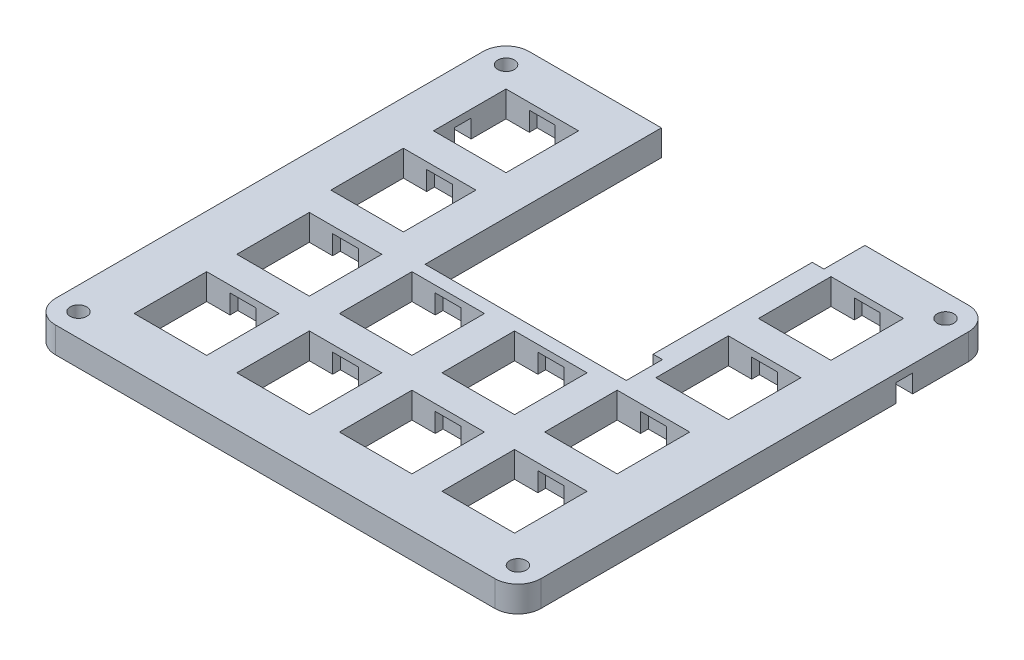
SolidWorks part; units mm, degrees
ref_plane "Front Plane" through (0, 0, 0) normal (0, 0, 1) x (1, 0, 0)
ref_plane "Top Plane" through (0, 0, 0) normal (0, 1, 0) x (1, 0, 0)
ref_plane "Right Plane" through (0, 0, 0) normal (1, 0, 0) x (0, 0, -1)
sketch "Sketch2" plane through (0, 0, 0) normal (0, 1, 0) x (1, 0, 0)
  line L6 (-46.8585, -41.275) -> (-46.8585, 41.275)
  line L8 (46.8585, -41.275) -> (46.8585, 41.275)
  line L9 (42.418, -45.7155) -> (-42.418, -45.7155)
  line L10 (-42.418, 45.7155) -> (-16.8754, 45.7155)
  line L12 (22.418, 41.275) -> (22.418, 39.575)
  line L13 (22.418, 39.575) -> (22.418, 37.7973)
  line L16 (42.418, 27.292) -> (38.3626, 27.292)
  line L18 (42.418, 30.492) -> (38.3626, 30.492)
  line L19 (42.418, 30.492) -> (46.218, 30.492)
  line L20 (46.218, 30.492) -> (46.218, 27.292)
  line L21 (46.218, 27.292) -> (42.418, 27.292)
  line L24 (-46.218, 28.892) -> (-46.218, 30.492)
  line L25 (-46.218, 30.492) -> (-38.3754, 30.492)
  line L26 (-46.218, 28.892) -> (-46.218, 27.292)
  line L27 (-46.218, 27.292) -> (-38.3754, 27.292)
  line L29 (20.1687, 37.7973) -> (20.1687, 9.575)
  line L30 (22.418, 37.7973) -> (20.1687, 37.7973)
  line L31 (20.1687, 9.575) -> (20.1687, 7.075)
  line L32 (20.1687, 7.075) -> (21.9687, 7.075)
  line L33 (-9.9124, 0.0949) -> (21.9687, 0.0949)
  line L35 (21.9687, 7.075) -> (21.9687, 0.0949)
  line L36 (22.418, 41.275) -> (22.418, 45.7155)
  line L38 (-16.8754, 30.2189) -> (-16.8754, 0.0949)
  line L39 (-16.8754, 0.0949) -> (-9.9124, 0.0949)
  line L40 (-16.8754, 30.2189) -> (-16.8754, 45.7155)
  line L41 (-31.3754, 37.2189) -> (-38.3754, 37.2189)
  line L42 (-38.3754, 37.2189) -> (-38.3754, 23.2189)
  line L43 (-38.3754, 23.2189) -> (-24.3754, 23.2189)
  line L44 (-24.3754, 23.2189) -> (-24.3754, 37.2189)
  line L45 (-24.3754, 37.2189) -> (-31.3754, 37.2189)
  line L47 (-38.3754, 10.4069) -> (-38.3754, 17.4069)
  line L48 (-38.3754, 17.4069) -> (-24.3754, 17.4069)
  line L49 (-24.3754, 17.4069) -> (-24.3754, 3.4069)
  line L50 (-24.3754, 3.4069) -> (-38.3754, 3.4069)
  line L51 (-38.3754, 3.4069) -> (-38.3754, 10.4069)
  line L53 (-36.7244, -9.4051) -> (-36.7244, -2.4051)
  line L54 (-36.7244, -2.4051) -> (-22.7244, -2.4051)
  line L55 (-22.7244, -2.4051) -> (-22.7244, -16.4051)
  line L56 (-22.7244, -16.4051) -> (-36.7244, -16.4051)
  line L57 (-36.7244, -16.4051) -> (-36.7244, -9.4051)
  line L59 (-36.7244, -29.2171) -> (-36.7244, -22.2171)
  line L60 (-36.7244, -22.2171) -> (-22.7244, -22.2171)
  line L61 (-22.7244, -22.2171) -> (-22.7244, -36.2171)
  line L62 (-22.7244, -36.2171) -> (-36.7244, -36.2171)
  line L63 (-36.7244, -36.2171) -> (-36.7244, -29.2171)
  line L65 (-9.9124, -22.2171) -> (-2.9124, -22.2171)
  line L66 (-2.9124, -22.2171) -> (-2.9124, -36.2171)
  line L67 (-2.9124, -36.2171) -> (-16.9124, -36.2171)
  line L68 (-16.9124, -36.2171) -> (-16.9124, -22.2171)
  line L69 (-16.9124, -22.2171) -> (-9.9124, -22.2171)
  line L71 (-9.9124, -16.4051) -> (-2.9124, -16.4051)
  line L72 (-2.9124, -16.4051) -> (-2.9124, -2.4051)
  line L73 (-2.9124, -2.4051) -> (-16.9124, -2.4051)
  line L74 (-16.9124, -2.4051) -> (-16.9124, -16.4051)
  line L75 (-16.9124, -16.4051) -> (-9.9124, -16.4051)
  line L77 (9.8996, -2.4051) -> (2.8996, -2.4051)
  line L78 (2.8996, -2.4051) -> (2.8996, -16.4051)
  line L79 (2.8996, -16.4051) -> (16.8996, -16.4051)
  line L80 (16.8996, -16.4051) -> (16.8996, -2.4051)
  line L81 (16.8996, -2.4051) -> (9.8996, -2.4051)
  line L83 (9.8996, -22.2171) -> (2.8996, -22.2171)
  line L84 (2.8996, -22.2171) -> (2.8996, -36.2171)
  line L85 (2.8996, -36.2171) -> (16.8996, -36.2171)
  line L86 (16.8996, -36.2171) -> (16.8996, -22.2171)
  line L87 (16.8996, -22.2171) -> (9.8996, -22.2171)
  line L89 (36.7116, -29.2171) -> (36.7116, -22.2171)
  line L90 (36.7116, -22.2171) -> (22.7116, -22.2171)
  line L91 (22.7116, -22.2171) -> (22.7116, -36.2171)
  line L92 (22.7116, -36.2171) -> (36.7116, -36.2171)
  line L93 (36.7116, -36.2171) -> (36.7116, -29.2171)
  line L95 (29.7116, -2.4051) -> (22.7116, -2.4051)
  line L96 (22.7116, -2.4051) -> (22.7116, -16.4051)
  line L97 (22.7116, -16.4051) -> (36.7116, -16.4051)
  line L98 (36.7116, -16.4051) -> (36.7116, -2.4051)
  line L99 (36.7116, -2.4051) -> (29.7116, -2.4051)
  line L101 (38.3626, 10.4069) -> (38.3626, 17.4069)
  line L102 (38.3626, 17.4069) -> (24.3626, 17.4069)
  line L103 (24.3626, 17.4069) -> (24.3626, 3.4069)
  line L104 (24.3626, 3.4069) -> (38.3626, 3.4069)
  line L105 (38.3626, 3.4069) -> (38.3626, 10.4069)
  line L106 (38.3626, 30.2189) -> (38.3626, 23.2189)
  line L107 (38.3626, 23.2189) -> (24.3626, 23.2189)
  line L108 (24.3626, 23.2189) -> (24.3626, 37.2189)
  line L109 (24.3626, 37.2189) -> (38.3626, 37.2189)
  line L110 (38.3626, 37.2189) -> (38.3626, 30.2189)
  line L111 (22.418, 45.7155) -> (42.418, 45.7155)
  arc A0 (-42.418, 45.7155) -> (-46.8585, 41.275) centre (-42.418, 41.275) ccw
  arc A1 (42.418, 45.7155) -> (46.8585, 41.275) centre (42.418, 41.275) cw
  arc A2 (-46.8585, -41.275) -> (-42.418, -45.7155) centre (-42.418, -41.275) ccw
  arc A3 (46.8585, -41.275) -> (42.418, -45.7155) centre (42.418, -41.275) cw
  circle A4 centre (42.418, 41.275) radius 1.6
  circle A5 centre (-42.418, 41.275) radius 1.6
  circle A6 centre (-42.418, -41.275) radius 1.6
  circle A7 centre (42.418, -41.275) radius 1.6
extrude "Boss-Extrude1" add sketch "Sketch2" along normal blind 5 contours A3 L8 A1 L111 L36 L12 L13 L30 L29 L31 L32 L35 L33 L39 L38 L40 L10 A0 L6 A2 L9 A7 A6 A5 A4 L105 L104 L103 L102 L101 L99 L98 L97 L96 L95 L93 L92 L91 L90 L89 L87 L86 L85 | L42 L25 L24 L26 L27 | L18 L110 L106 L16 L21 L20 L19
sketch "Sketch3" plane through (0, 0, 0) normal (0, -1, 0) x (1, 0, 0)
  line L0 (42.418, -41.275) -> (42.418, -28.892)
  line L1 (42.418, -28.892) -> (46.218, -28.892)
  line L3 (46.218, -27.292) -> (38.3626, -27.292)
  line L4 (38.3626, -37.2189) -> (38.3626, -23.2189) construction
  line L6 (46.218, -30.492) -> (38.3626, -30.492)
  line L7 (38.3626, -30.492) -> (38.3626, -27.292)
  line L8 (-42.418, -41.275) -> (-42.418, -28.892)
  line L9 (-42.418, -28.892) -> (-46.218, -28.892)
  line L12 (-46.218, -27.292) -> (-38.3754, -27.292)
  line L13 (-38.3754, -37.2189) -> (-38.3754, -23.2189) construction
  line L14 (-46.218, -30.492) -> (-38.3754, -30.492)
  line L15 (-38.3754, -30.492) -> (-38.3754, -27.292)
  line L16 (-46.218, -27.292) -> (-46.8585, -27.292)
  line L17 (-46.8585, 41.275) -> (-46.8585, -41.275) construction
  line L18 (-46.8585, -27.292) -> (-46.8585, -30.492)
  line L19 (-46.8585, -30.492) -> (-46.218, -30.492)
  line L20 (46.218, -27.292) -> (46.8585, -27.292)
  line L21 (46.8585, 41.275) -> (46.8585, -41.275) construction
  line L22 (46.8585, -27.292) -> (46.8585, -30.492)
  line L23 (46.8585, -30.492) -> (46.218, -30.492)
extrude "Cut-Extrude1" cut sketch "Sketch3" against normal blind 3.5
sketch "Sketch4" plane through (0, 0, 0) normal (0, -1, 0) x (1, 0, 0)
  line L0 (31.3626, -37.2189) -> (31.3626, -38.7189)
  line L1 (24.3626, -37.2189) -> (38.3626, -37.2189) construction
  line L2 (31.3626, -38.7189) -> (28.8626, -38.7189)
  line L3 (28.8626, -38.7189) -> (28.8626, -37.2189)
  line L4 (28.8626, -37.2189) -> (33.8626, -37.2189)
  line L5 (33.8626, -37.2189) -> (33.8626, -38.7189)
  line L6 (33.8626, -38.7189) -> (31.3626, -38.7189)
  line L7 (31.3626, -23.2189) -> (31.3626, -21.7189)
  line L8 (38.3626, -23.2189) -> (24.3626, -23.2189) construction
  line L9 (31.3626, -21.7189) -> (33.8626, -21.7189)
  line L10 (33.8626, -21.7189) -> (33.8626, -23.2189)
  line L11 (33.8626, -23.2189) -> (28.8626, -23.2189)
  line L12 (28.8626, -23.2189) -> (28.8626, -21.7189)
  line L13 (28.8626, -21.7189) -> (31.3626, -21.7189)
  line L14 (31.3626, -17.4069) -> (31.3626, -18.9069)
  line L15 (38.3626, -17.4069) -> (24.3626, -17.4069) construction
  line L16 (31.3626, -18.9069) -> (33.8626, -18.9069)
  line L17 (33.8626, -18.9069) -> (33.8626, -17.4069)
  line L18 (33.8626, -17.4069) -> (28.8626, -17.4069)
  line L19 (28.8626, -17.4069) -> (28.8626, -18.9069)
  line L20 (28.8626, -18.9069) -> (31.3626, -18.9069)
  line L21 (31.3626, -3.4069) -> (31.3626, -1.9069)
  line L22 (24.3626, -3.4069) -> (38.3626, -3.4069) construction
  line L23 (31.3626, -1.9069) -> (33.8626, -1.9069)
  line L24 (33.8626, -1.9069) -> (33.8626, -3.4069)
  line L25 (33.8626, -3.4069) -> (28.8626, -3.4069)
  line L26 (28.8626, -3.4069) -> (28.8626, -1.9069)
  line L27 (28.8626, -1.9069) -> (31.3626, -1.9069)
  line L28 (29.7116, 2.4051) -> (29.7116, 0.9051)
  line L29 (36.7116, 2.4051) -> (22.7116, 2.4051) construction
  line L30 (29.7116, 0.9051) -> (32.2116, 0.9051)
  line L31 (32.2116, 0.9051) -> (32.2116, 2.4051)
  line L32 (32.2116, 2.4051) -> (27.2116, 2.4051)
  line L33 (27.2116, 2.4051) -> (27.2116, 0.9051)
  line L34 (27.2116, 0.9051) -> (29.7116, 0.9051)
  line L35 (29.7116, 16.4051) -> (29.7116, 17.9051)
  line L36 (22.7116, 16.4051) -> (36.7116, 16.4051) construction
  line L37 (29.7116, 17.9051) -> (32.2116, 17.9051)
  line L38 (32.2116, 17.9051) -> (32.2116, 16.4051)
  line L39 (32.2116, 16.4051) -> (27.2116, 16.4051)
  line L40 (27.2116, 16.4051) -> (27.2116, 17.9051)
  line L41 (27.2116, 17.9051) -> (29.7116, 17.9051)
  line L42 (29.7116, 22.2171) -> (29.7116, 20.7171)
  line L43 (36.7116, 22.2171) -> (22.7116, 22.2171) construction
  line L44 (29.7116, 20.7171) -> (32.2116, 20.7171)
  line L45 (32.2116, 20.7171) -> (32.2116, 22.2171)
  line L46 (32.2116, 22.2171) -> (27.2116, 22.2171)
  line L47 (27.2116, 22.2171) -> (27.2116, 20.7171)
  line L48 (27.2116, 20.7171) -> (29.7116, 20.7171)
  line L49 (29.7116, 36.2171) -> (29.7116, 37.7171)
  line L50 (22.7116, 36.2171) -> (36.7116, 36.2171) construction
  line L51 (29.7116, 37.7171) -> (32.2116, 37.7171)
  line L52 (32.2116, 37.7171) -> (32.2116, 36.2171)
  line L53 (32.2116, 36.2171) -> (27.2116, 36.2171)
  line L54 (27.2116, 36.2171) -> (27.2116, 37.7171)
  line L55 (27.2116, 37.7171) -> (29.7116, 37.7171)
  line L56 (9.8996, 2.4051) -> (9.8996, 0.9051)
  line L57 (16.8996, 2.4051) -> (2.8996, 2.4051) construction
  line L58 (9.8996, 0.9051) -> (12.3996, 0.9051)
  line L59 (12.3996, 0.9051) -> (12.3996, 2.4051)
  line L60 (12.3996, 2.4051) -> (7.3996, 2.4051)
  line L61 (7.3996, 2.4051) -> (7.3996, 0.9051)
  line L62 (7.3996, 0.9051) -> (9.8996, 0.9051)
  line L63 (9.8996, 16.4051) -> (9.8996, 17.9051)
  line L64 (2.8996, 16.4051) -> (16.8996, 16.4051) construction
  line L65 (9.8996, 17.9051) -> (7.3996, 17.9051)
  line L66 (7.3996, 17.9051) -> (7.3996, 16.4051)
  line L67 (7.3996, 16.4051) -> (12.3996, 16.4051)
  line L68 (12.3996, 16.4051) -> (12.3996, 17.9051)
  line L69 (12.3996, 17.9051) -> (9.8996, 17.9051)
  line L70 (9.8996, 22.2171) -> (9.8996, 20.7171)
  line L71 (16.8996, 22.2171) -> (2.8996, 22.2171) construction
  line L72 (9.8996, 20.7171) -> (7.3996, 20.7171)
  line L73 (7.3996, 20.7171) -> (7.3996, 22.2171)
  line L74 (7.3996, 22.2171) -> (12.3996, 22.2171)
  line L75 (12.3996, 22.2171) -> (12.3996, 20.7171)
  line L76 (12.3996, 20.7171) -> (9.8996, 20.7171)
  line L77 (9.8996, 36.2171) -> (9.8996, 37.7171)
  line L78 (2.8996, 36.2171) -> (16.8996, 36.2171) construction
  line L79 (9.8996, 37.7171) -> (7.3996, 37.7171)
  line L80 (7.3996, 37.7171) -> (7.3996, 36.2171)
  line L81 (7.3996, 36.2171) -> (12.3996, 36.2171)
  line L82 (12.3996, 36.2171) -> (12.3996, 37.7171)
  line L83 (12.3996, 37.7171) -> (9.8996, 37.7171)
  line L84 (-9.9124, 2.4051) -> (-9.9124, 0.9051)
  line L85 (-2.9124, 2.4051) -> (-16.9124, 2.4051) construction
  line L86 (-9.9124, 0.9051) -> (-12.4124, 0.9051)
  line L87 (-12.4124, 0.9051) -> (-12.4124, 2.4051)
  line L88 (-12.4124, 2.4051) -> (-7.4124, 2.4051)
  line L89 (-7.4124, 2.4051) -> (-7.4124, 0.9051)
  line L90 (-7.4124, 0.9051) -> (-9.9124, 0.9051)
  line L91 (-9.9124, 16.4051) -> (-9.9124, 17.9051)
  line L92 (-16.9124, 16.4051) -> (-2.9124, 16.4051) construction
  line L93 (-9.9124, 17.9051) -> (-12.4124, 17.9051)
  line L94 (-12.4124, 17.9051) -> (-12.4124, 16.4051)
  line L95 (-12.4124, 16.4051) -> (-7.4124, 16.4051)
  line L96 (-7.4124, 16.4051) -> (-7.4124, 17.9051)
  line L97 (-7.4124, 17.9051) -> (-9.9124, 17.9051)
  line L98 (-9.9124, 22.2171) -> (-9.9124, 20.7171)
  line L99 (-16.9124, 22.2171) -> (-2.9124, 22.2171) construction
  line L100 (-9.9124, 20.7171) -> (-7.4124, 20.7171)
  line L101 (-7.4124, 20.7171) -> (-7.4124, 22.2171)
  line L102 (-7.4124, 22.2171) -> (-12.4124, 22.2171)
  line L103 (-12.4124, 22.2171) -> (-12.4124, 20.7171)
  line L104 (-12.4124, 20.7171) -> (-9.9124, 20.7171)
  line L105 (-9.9124, 36.2171) -> (-9.9124, 37.7171)
  line L106 (-2.9124, 36.2171) -> (-16.9124, 36.2171) construction
  line L107 (-9.9124, 37.7171) -> (-7.4124, 37.7171)
  line L108 (-7.4124, 37.7171) -> (-7.4124, 36.2171)
  line L109 (-7.4124, 36.2171) -> (-12.4124, 36.2171)
  line L110 (-12.4124, 36.2171) -> (-12.4124, 37.7171)
  line L111 (-12.4124, 37.7171) -> (-9.9124, 37.7171)
  line L112 (-31.3754, -37.2189) -> (-31.3754, -38.7189)
  line L113 (-24.3754, -37.2189) -> (-38.3754, -37.2189) construction
  line L114 (-31.3754, -38.7189) -> (-33.8754, -38.7189)
  line L115 (-33.8754, -38.7189) -> (-33.8754, -37.2189)
  line L116 (-33.8754, -37.2189) -> (-28.8754, -37.2189)
  line L117 (-28.8754, -37.2189) -> (-28.8754, -38.7189)
  line L118 (-28.8754, -38.7189) -> (-31.3754, -38.7189)
  line L119 (-31.3754, -23.2189) -> (-31.3754, -21.7189)
  line L120 (-38.3754, -23.2189) -> (-24.3754, -23.2189) construction
  line L121 (-31.3754, -21.7189) -> (-33.8754, -21.7189)
  line L122 (-33.8754, -21.7189) -> (-33.8754, -23.2189)
  line L123 (-33.8754, -23.2189) -> (-28.8754, -23.2189)
  line L124 (-28.8754, -23.2189) -> (-28.8754, -21.7189)
  line L125 (-31.3754, -21.7189) -> (-28.8754, -21.7189)
  line L126 (-31.3754, -17.4069) -> (-31.3754, -18.9069)
  line L127 (-38.3754, -17.4069) -> (-24.3754, -17.4069) construction
  line L128 (-31.3754, -18.9069) -> (-28.8754, -18.9069)
  line L129 (-28.8754, -18.9069) -> (-28.8754, -17.4069)
  line L130 (-28.8754, -17.4069) -> (-33.8754, -17.4069)
  line L131 (-33.8754, -17.4069) -> (-33.8754, -18.9069)
  line L132 (-33.8754, -18.9069) -> (-31.3754, -18.9069)
  line L133 (-31.3754, -3.4069) -> (-28.8754, -3.4069)
  line L134 (-24.3754, -3.4069) -> (-38.3754, -3.4069) construction
  line L135 (-28.8754, -3.4069) -> (-28.8754, -1.9069)
  line L136 (-28.8754, -1.9069) -> (-33.8754, -1.9069)
  line L137 (-33.8754, -1.9069) -> (-33.8754, -3.4069)
  line L138 (-33.8754, -3.4069) -> (-31.3754, -3.4069)
  line L139 (-29.7244, 2.4051) -> (-29.7244, 0.9051)
  line L140 (-36.7244, 2.4051) -> (-22.7244, 2.4051) construction
  line L141 (-29.7244, 0.9051) -> (-27.2244, 0.9051)
  line L142 (-27.2244, 0.9051) -> (-27.2244, 2.4051)
  line L143 (-27.2244, 2.4051) -> (-32.2244, 2.4051)
  line L144 (-32.2244, 2.4051) -> (-32.2244, 0.9051)
  line L145 (-32.2244, 0.9051) -> (-29.7244, 0.9051)
  line L146 (-29.7244, 16.4051) -> (-29.7244, 17.9051)
  line L147 (-22.7244, 16.4051) -> (-36.7244, 16.4051) construction
  line L148 (-29.7244, 17.9051) -> (-27.2244, 17.9051)
  line L149 (-27.2244, 17.9051) -> (-27.2244, 16.4051)
  line L150 (-27.2244, 16.4051) -> (-32.2244, 16.4051)
  line L151 (-32.2244, 16.4051) -> (-32.2244, 17.9051)
  line L152 (-32.2244, 17.9051) -> (-29.7244, 17.9051)
  line L153 (-29.7244, 22.2171) -> (-29.7244, 20.7171)
  line L154 (-36.7244, 22.2171) -> (-22.7244, 22.2171) construction
  line L155 (-29.7244, 20.7171) -> (-27.2244, 20.7171)
  line L156 (-27.2244, 20.7171) -> (-27.2244, 22.2171)
  line L157 (-27.2244, 22.2171) -> (-32.2244, 22.2171)
  line L158 (-32.2244, 22.2171) -> (-32.2244, 20.7171)
  line L159 (-32.2244, 20.7171) -> (-29.7244, 20.7171)
  line L160 (-29.7244, 36.2171) -> (-29.7244, 37.7171)
  line L161 (-22.7244, 36.2171) -> (-36.7244, 36.2171) construction
  line L162 (-29.7244, 37.7171) -> (-27.2244, 37.7171)
  line L163 (-27.2244, 37.7171) -> (-27.2244, 36.2171)
  line L164 (-27.2244, 36.2171) -> (-32.2244, 36.2171)
  line L165 (-32.2244, 36.2171) -> (-32.2244, 37.7171)
  line L166 (-32.2244, 37.7171) -> (-29.7244, 37.7171)
extrude "Cut-Extrude2" cut sketch "Sketch4" against normal blind 3.7 contours L6 L5 L4 L0 | L4 L3 L2 L0 | L11 L10 L9 L7 | L13 L12 L11 L7 | L25 L24 L23 L21 | L19 L20 L14 L18 | L17 L18 L14 L16 | L27 L26 L25 L21 | L31 L32 L28 L30 | L33 L34 L28 L32 | L39 L38 L37 L35 | L41 L40 L39 L35 | L45 L46 L42 L44 | L47 L48 L42 L46 | L53 L52 L51 L49 | L55 L54 L53 L49 | L82 L83 L77 L81 | L80 L81 L77 L79 | L74 L73 L72 L70 | L76 L75 L74 L70 | L68 L69 L63 L67 | L66 L67 L63 L65 | L59 L60 L56 L58 | L61 L62 L56 L60 | L90 L89 L88 L84 | L88 L87 L86 L84 | L96 L97 L91 L95 | L94 L95 L91 L93 | L101 L102 L98 L100 | L103 L104 L98 L102 | L109 L108 L107 L105 | L111 L110 L109 L105 | L150 L149 L148 L146 | L152 L151 L150 L146 | L158 L159 L153 L157 | L156 L157 L153 L155 | L164 L163 L162 L160 | L166 L165 L164 L160 | L142 L143 L139 L141 | L144 L145 L139 L143 | L137 L138 L133 L135 L136 | L131 L132 L126 L130 | L129 L130 L126 L128 | L122 L123 L119 L121 | L125 L119 L123 L124 | L118 L117 L116 L112 | L116 L115 L114 L112
